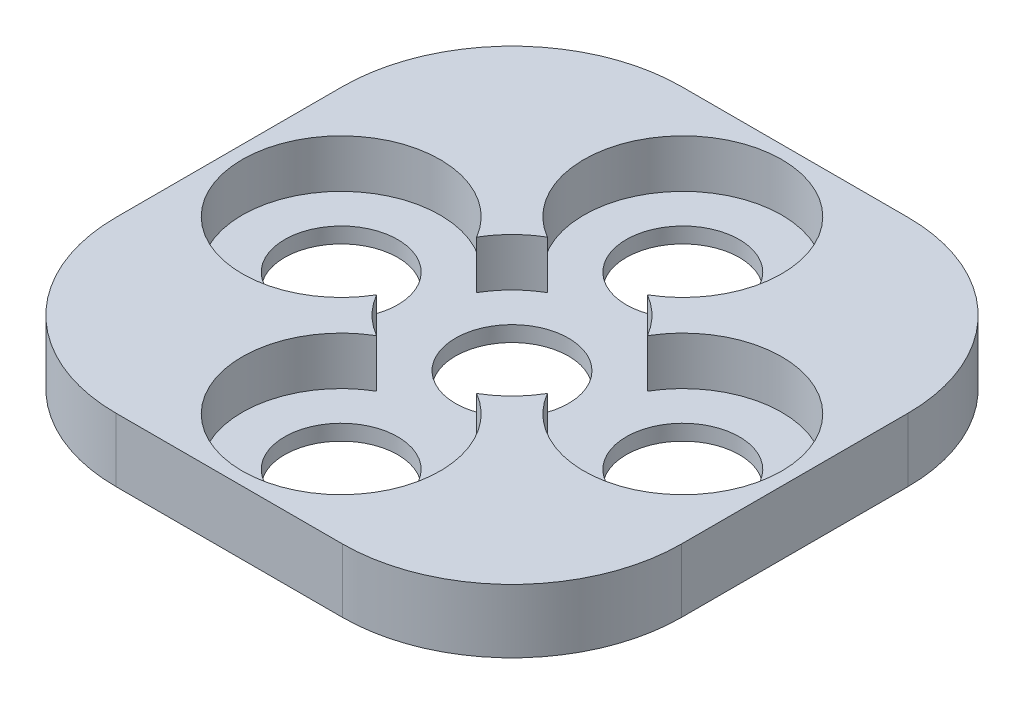
SolidWorks part; units mm, degrees
material "Pine"
ref_plane "Front Plane" through (0, 0, 0) normal (0, 0, 1) x (1, 0, 0)
ref_plane "Top Plane" through (0, 0, 0) normal (0, 1, 0) x (1, 0, 0)
ref_plane "Right Plane" through (0, 0, 0) normal (1, 0, 0) x (0, 0, -1)
sketch "Sketch1" plane through (0, 0, 0) normal (0, 1, 0) x (1, 0, 0)
  line L1 (0, 0) -> (254, 0)
  line L2 (0, 0) -> (0, 254)
  line L3 (0, 254) -> (254, 254)
  line L4 (254, 0) -> (254, 254)
  dimension "D1" = 254
  dimension "D2" = 254
extrude "Boss-Extrude1" add sketch "Sketch1" along normal blind 28.575
sketch "Sketch2" plane through (0, 28.575, 0) normal (0, 1, 0) x (1, 0, 0)
  line L0 (0, 0) -> (254, 0) construction
  arc A0 (149.4672, 88.646) -> (165.354, 104.5328) centre (127, 127) ccw
  arc A1 (104.5328, 88.646) -> (149.4672, 88.646) centre (127, 50.292) ccw
  arc A2 (88.646, 149.4672) -> (88.646, 104.5328) centre (50.292, 127) ccw
  arc A3 (149.4672, 88.646) -> (165.354, 104.5328) centre (127, 127) ccw
  arc A4 (149.4672, 165.354) -> (104.5328, 165.354) centre (127, 203.708) ccw
  arc A5 (149.4672, 88.646) -> (165.354, 104.5328) centre (127, 127) ccw
  arc A6 (165.354, 104.5328) -> (165.354, 149.4672) centre (203.708, 127) ccw
  arc A7 (149.4672, 88.646) -> (165.354, 104.5328) centre (127, 127) ccw
  arc A8 (88.646, 104.5328) -> (104.5328, 88.646) centre (127, 127) ccw
  arc A9 (88.646, 104.5328) -> (104.5328, 88.646) centre (127, 127) ccw
  arc A10 (88.646, 104.5328) -> (104.5328, 88.646) centre (127, 127) ccw
  arc A11 (88.646, 104.5328) -> (104.5328, 88.646) centre (127, 127) ccw
  arc A12 (104.5328, 165.354) -> (88.646, 149.4672) centre (127, 127) ccw
  arc A13 (104.5328, 165.354) -> (88.646, 149.4672) centre (127, 127) ccw
  arc A14 (104.5328, 165.354) -> (88.646, 149.4672) centre (127, 127) ccw
  arc A15 (104.5328, 165.354) -> (88.646, 149.4672) centre (127, 127) ccw
  arc A16 (165.354, 149.4672) -> (149.4672, 165.354) centre (127, 127) ccw
  arc A17 (165.354, 149.4672) -> (149.4672, 165.354) centre (127, 127) ccw
  arc A18 (165.354, 149.4672) -> (149.4672, 165.354) centre (127, 127) ccw
  arc A19 (165.354, 149.4672) -> (149.4672, 165.354) centre (127, 127) ccw
  point P18 (127, 127)
  dimension "D1" = 88.9
  dimension "D4" = 88.9
  dimension "D2" = 76.708
  dimension "D3" = 127
  dimension "D5" = 4
extrude "Cut-Extrude1" cut sketch "Sketch2" against normal blind 21.59 contours A6 A16 A4 A12 A2 A8 A1 A0
sketch "Sketch3" plane through (0, 6.985, 0) normal (0, 1, 0) x (1, 0, 0)
  circle A0 centre (127, 127) radius 25.4
  circle A1 centre (127, 50.292) radius 25.4
  circle A2 centre (50.292, 127) radius 25.4
  circle A3 centre (127, 203.708) radius 25.4
  circle A4 centre (203.708, 127) radius 25.4
  dimension "D1" = 50.8
extrude "Cut-Extrude2" cut sketch "Sketch3" against normal blind 16.51
fillet "Fillet1" radius 76.2 4 edges at (0, 14.2875, 0) (0, 14.2875, -254) (254, 14.2875, -254) (254, 14.2875, 0)
